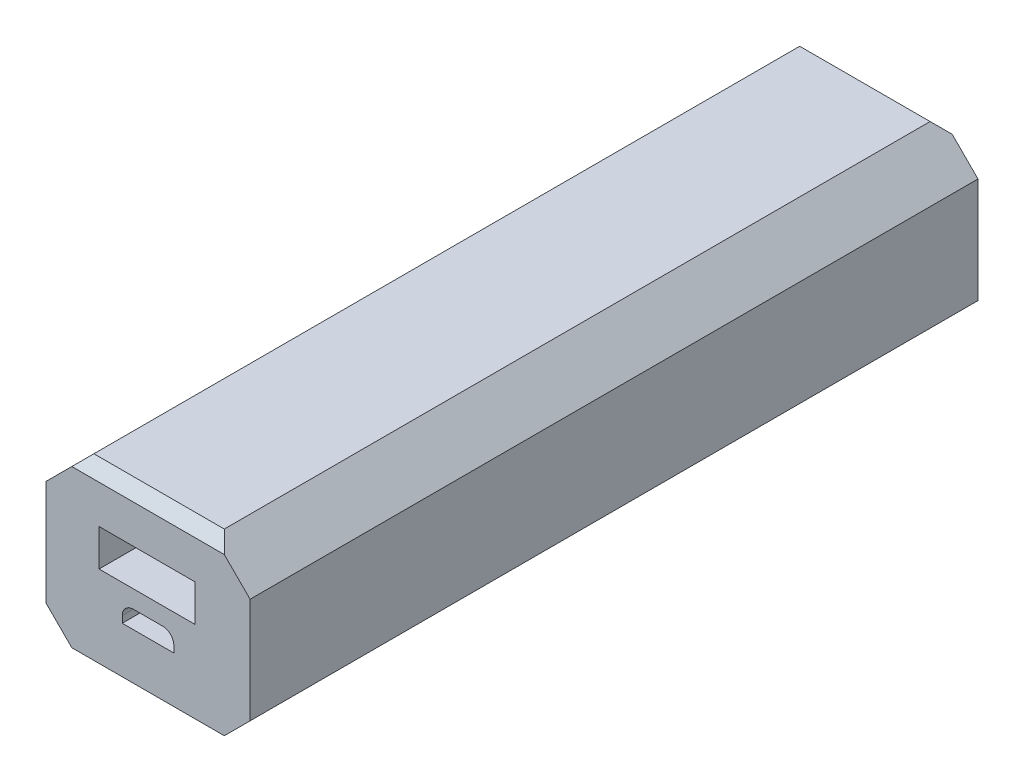
SolidWorks part; units mm, degrees
ref_plane "Front Plane" through (0, 0, 0) normal (0, 0, 1) x (1, 0, 0)
ref_plane "Top Plane" through (0, 0, 0) normal (0, 1, 0) x (1, 0, 0)
ref_plane "Right Plane" through (0, 0, 0) normal (1, 0, 0) x (0, 0, -1)
sketch "Sketch1" plane through (0, 0, 0) normal (0, 0, 1) x (1, 0, 0)
  line L1 (0, 0) -> (27.7, 0)
  line L2 (0, 0) -> (0, 24.3)
  line L3 (0, 24.3) -> (27.7, 24.3)
  line L4 (27.7, 0) -> (27.7, 24.3)
  dimension "D1" = 24.3
  dimension "D2" = 27.7
extrude "Boss-Extrude1" add sketch "Sketch1" along normal blind 98.8
chamfer "Chamfer1" distance 5 angle 45 4 edges at (0, 24.3, 49.4) (0, 0, 49.4) (27.7, 0, 49.4) (27.7, 24.3, 49.4)
chamfer "Chamfer2" distance 1.5 angle 45 4 edges at (13.85, 0, 0) (13.85, 0, 98.8) (13.85, 24.3, 0) (13.85, 24.3, 98.8)
sketch "Sketch2" plane through (0, 0, 98.8) normal (0, 0, 1) x (1, 0, 0)
  line L0 (22.7, 0) -> (5, 0) construction
  line L1 (7.2, 17.6004) -> (20.2, 17.6004)
  line L2 (7.2, 17.6004) -> (7.2, 12.6004)
  line L3 (7.2, 12.6004) -> (20.2, 12.6004)
  line L4 (20.2, 17.6004) -> (20.2, 12.6004)
  line L5 (27.7, 5) -> (27.7, 19.3) construction
  dimension "D1" = 12.6004
  dimension "D2" = 7.5
  dimension "D3" = 13
  dimension "D4" = 5
extrude "Cut-Extrude1" cut sketch "Sketch2" against normal blind 15
sketch "Sketch3" plane through (0, 0, 98.8) normal (0, 0, 1) x (1, 0, 0)
  line L0 (7.2, 12.6004) -> (20.2, 12.6004) construction
  line L1 (10.35, 10.2004) -> (17.35, 10.2004)
  line L2 (10.35, 10.2004) -> (10.35, 7.8004)
  line L3 (10.35, 7.8004) -> (17.35, 7.8004)
  line L4 (17.35, 10.2004) -> (17.35, 7.8004)
  line L5 (27.7, 5) -> (27.7, 19.3) construction
  dimension "D1" = 2.4
  dimension "D2" = 10.35
  dimension "D3" = 7
  dimension "D4" = 2.4
extrude "Cut-Extrude3" cut sketch "Sketch3" against normal blind 10
fillet "Fillet1" radius 1.5 2 edges at (17.35, 10.2004, 93.8) (10.35, 10.2004, 93.8)
